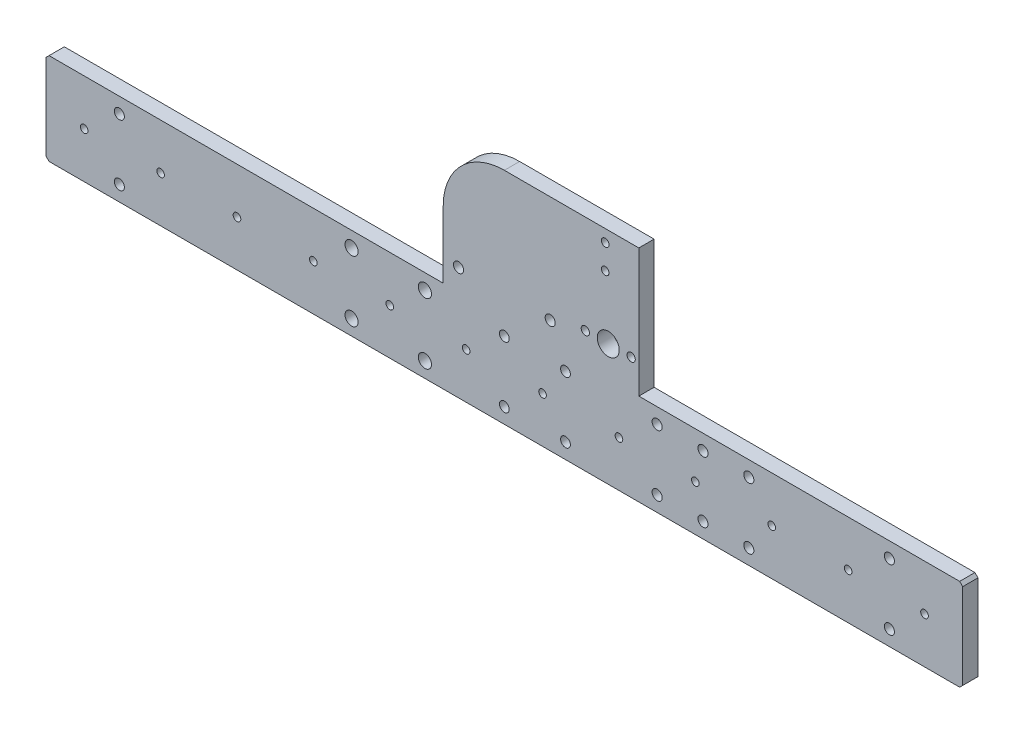
SolidWorks part; units mm, degrees
material "5052-O"
ref_plane "前基準面" through (0, 0, 0) normal (0, 0, 1) x (1, 0, 0)
ref_plane "上基準面" through (0, 0, 0) normal (0, 1, 0) x (1, 0, 0)
ref_plane "右基準面" through (0, 0, 0) normal (1, 0, 0) x (0, 0, -1)
sketch "草圖1" plane through (0, 0, 0) normal (0, 0, 1) x (1, 0, 0)
  line L1 (-150, -15) -> (150, -15)
  line L2 (-150, -15) -> (-150, 15)
  line L3 (-150, 15) -> (150, 15)
  line L4 (150, -15) -> (150, 15)
  line L5 (-150, -15) -> (150, 15) construction
  line L6 (-150, 15) -> (150, -15) construction
  point P0 (0, 0)
  dimension "D1" = 300
  dimension "D2" = 30
extrude "填料-伸長1" add sketch "草圖1" along normal blind 5
chamfer "導角1" distance 1 angle 45 4 edges at (150, -15, 2.5) (150, 15, 2.5) (-150, -15, 2.5) (-150, 15, 2.5)
hole_wizard "M3 餘隙孔1" positions "草圖7" profile "草圖8" hole size "M3" standard "Ansi Metric" end condition through all
sketch "草圖7" plane through (0, 0, 5) normal (0, 0, 1) x (1, 0, 0)
  line L0 (0, 0) -> (10, 0) construction
  line L4 (0, -10) -> (20, -10) construction
  line L5 (0, -10) -> (0, 10) construction
  line L6 (0, 10) -> (20, 10) construction
  line L7 (20, -10) -> (20, 10) construction
  line L8 (0, -10) -> (20, 10) construction
  line L9 (0, 10) -> (20, -10) construction
  point P9 (20, 10)
  point P60 (0, -10)
  point P61 (0, 10)
  point P62 (20, -10)
  dimension "D1" = 10
  dimension "D2" = 20
  dimension "D3" = 20
sketch "草圖8" plane through (20, -10, 5) normal (1, 0, 0) x (0, -1, 0)
  line L0 (0, 0) -> (0, 5)
  line L1 (0, 5) -> (1.6, 5)
  line L2 (1.6, 5) -> (1.6, 0)
  line L5 (1.6, 0) -> (0, 0)
  line L11 (0, -6.35) -> (0, 107.95) construction
  dimension "貫穿孔直徑" = 3.2
  dimension "貫穿孔深度" = 5
hole_wizard "M3x0.5 螺紋孔1" positions "草圖3" profile "草圖4" tap size "M3x0.5" standard "Ansi Metric" end condition through all
sketch "草圖3" plane through (0, 0, 5) normal (0, 0, 1) x (1, 0, 0)
  line L0 (-12.5, 0) -> (12.5, 0) construction
  point P0 (-12.5, 0)
  dimension "D1" = 25
sketch "草圖4" plane through (-12.5, 0, 5) normal (1, 0, 0) x (0, -1, 0)
  line L0 (0, 0) -> (0, 5)
  line L1 (0, 5) -> (1.25, 5)
  line L2 (1.25, 5) -> (1.25, 0)
  line L5 (1.25, 0) -> (0, 0)
  line L11 (0, -6.35) -> (0, 107.95) construction
  dimension "貫穿螺孔鑽直徑" = 2.5
  dimension "貫穿螺孔鑽深度" = 5
hole_wizard "M4x0.7 螺紋孔1" positions "草圖9" profile "草圖10" tap size "M4x0.7" standard "Ansi Metric" end condition through all
sketch "草圖9" plane through (0, 0, 5) normal (0, 0, 1) x (1, 0, 0)
  line L1 (50, -10) -> (80, -10) construction
  line L2 (50, -10) -> (50, 10) construction
  line L3 (50, 10) -> (80, 10) construction
  line L4 (80, -10) -> (80, 10) construction
  line L5 (50, -10) -> (80, 10) construction
  line L6 (50, 10) -> (80, -10) construction
  line L7 (0, 0) -> (65, 0) construction
  point P2 (80, 10)
  point P55 (50, -10)
  point P56 (50, 10)
  point P57 (80, -10)
  point P68 (65, 0)
  point P78 (65, 10)
  point P80 (65, -10)
  dimension "D1" = 30
  dimension "D2" = 20
  dimension "D3" = 65
sketch "草圖10" plane through (80, 10, 5) normal (1, 0, 0) x (0, -1, 0)
  line L0 (0, 0) -> (0, 5)
  line L1 (0, 5) -> (1.65, 5)
  line L2 (1.65, 5) -> (1.65, 0)
  line L5 (1.65, 0) -> (0, 0)
  line L11 (0, -6.35) -> (0, 107.95) construction
  dimension "砮 脸ふ苝 畖" = 3.3
  dimension "砮 脸ふ苝瞏 " = 5
hole_wizard "M4x0.7 螺紋孔2" positions "草圖11" profile "草圖12" tap size "M4x0.7" standard "Ansi Metric" end condition through all
sketch "草圖11" plane through (0, 0, 5) normal (0, 0, 1) x (1, 0, 0)
  line L0 (-150, 0) -> (-126, 0) construction
  line L1 (-150, 14) -> (-150, -14) construction
  line L4 (-126, -10) -> (-126, 10) construction
  point P9 (-126, -10)
  point P10 (-126, 10)
  dimension "D1" = 20
  dimension "D2" = 24
sketch "草圖12" plane through (-126, 10, 5) normal (1, 0, 0) x (0, -1, 0)
  line L0 (0, 0) -> (0, 5)
  line L1 (0, 5) -> (1.65, 5)
  line L2 (1.65, 5) -> (1.65, 0)
  line L5 (1.65, 0) -> (0, 0)
  line L11 (0, -6.35) -> (0, 107.95) construction
  dimension "貫穿螺孔鑽直徑" = 3.3
  dimension "貫穿螺孔鑽深度" = 5
pattern_linear "直線複製排列1" count 6 spacing 25 along (-1, 0, 0) count 7 spacing 25 along (1, 0, 0) of "M3x0.5 螺紋孔1"
mirror "鏡射1" about plane through (0, 0, 0) normal (1, 0, 0) of "M4x0.7 螺紋孔2"
sketch "草圖16" plane through (0, 0, 0) normal (0, 0, 1) x (1, 0, 0)
  line L0 (-20, 15) -> (44, 15)
  line L1 (149, 15) -> (-149, 15) construction
  line L4 (-20, 37) -> (-20, 15)
  line L5 (0, 0) -> (0, 57) construction
  line L9 (44, 15) -> (44, 57)
  line L10 (44, 57) -> (0, 57)
  arc A1 (-20, 37) -> (0, 57) centre (0, 37) cw
  point P7 (33.0842, 57)
  point P8 (38.8416, 57)
  dimension "D3" = 22
  dimension "D1" = 20
  dimension "D2" = 57
  dimension "D4" = 44
extrude "填料-伸長3" add sketch "草圖16" along normal through all
sketch "草圖13" plane through (0, 0, 0) normal (0, 0, 1) x (1, 0, 0)
  circle A1 centre (34, 24.8) radius 3.6
  point P8 (0, 0)
  dimension "D1" = 11.9701
  dimension "D2" = 7.2
  dimension "D3" = 24.8
  dimension "D4" = 34
  dimension "D5" = 34
extrude "除料-伸長2" cut sketch "草圖13" along normal through all
hole_wizard "M2.5 餘隙孔1" positions "草圖14" profile "草圖15" hole size "M2.5" standard "Ansi Metric" end condition through all
sketch "草圖14" plane through (0, 0, 5) normal (0, 0, 1) x (1, 0, 0)
  line L1 (26.5, 24.8) -> (41.5, 24.8) construction
  circle A2 centre (34, 24.8) radius 3.6 construction
  point P1 (26.5, 24.8)
  point P2 (41.5, 24.8)
  point P17 (34, 24.8)
  dimension "D1" = 15
sketch "草圖15" plane through (26.5, 24.8, 5) normal (1, 0, 0) x (0, -1, 0)
  line L0 (0, 0) -> (0, 5)
  line L1 (0, 5) -> (1.35, 5)
  line L2 (1.35, 5) -> (1.35, 0)
  line L5 (1.35, 0) -> (0, 0)
  line L11 (0, -6.35) -> (0, 107.95) construction
  dimension "貫穿孔直徑" = 2.7
  dimension "貫穿孔深度" = 5
hole_wizard "M4x0.7 螺紋孔3" positions "草圖19" profile "草圖20" tap size "M4x0.7" standard "Ansi Metric" end condition through all
sketch "草圖19" plane through (0, 0, 5) normal (0, 0, 1) x (1, 0, 0)
  line L0 (0, 57) -> (0, 22) construction
  line L4 (-15, 22) -> (15, 22) construction
  point P9 (-15, 22)
  point P10 (15, 22)
  point P17 (0, 0)
  point P18 (0, 53.6959)
  dimension "D1" = 30
  dimension "D2" = 22
sketch "草圖20" plane through (15, 22, 5) normal (1, 0, 0) x (0, -1, 0)
  line L0 (0, 0) -> (0, 5)
  line L1 (0, 5) -> (1.65, 5)
  line L2 (1.65, 5) -> (1.65, 0)
  line L5 (1.65, 0) -> (0, 0)
  line L11 (0, -6.35) -> (0, 107.95) construction
  dimension "貫穿螺孔鑽直徑" = 3.3
  dimension "貫穿螺孔鑽深度" = 5
hole_wizard "M4 餘隙孔1" positions "草圖21" profile "草圖22" hole size "M4" standard "Ansi Metric" end condition through all
sketch "草圖21" plane through (0, 0, 5) normal (0, 0, 1) x (1, 0, 0)
  line L0 (0, 0) -> (-38, 0) construction
  line L4 (-50, -10) -> (-26, -10) construction
  line L5 (-50, -10) -> (-50, 10) construction
  line L6 (-50, 10) -> (-26, 10) construction
  line L7 (-26, -10) -> (-26, 10) construction
  line L8 (-50, -10) -> (-26, 10) construction
  line L9 (-50, 10) -> (-26, -10) construction
  point P11 (-26, 10)
  point P60 (-50, -10)
  point P61 (-50, 10)
  point P62 (-26, -10)
  dimension "D1" = 38
  dimension "D2" = 24
  dimension "D3" = 20
sketch "草圖22" plane through (-26, -10, 5) normal (1, 0, 0) x (0, -1, 0)
  line L0 (0, 0) -> (0, 5)
  line L1 (0, 5) -> (2.15, 5)
  line L2 (2.15, 5) -> (2.15, 0)
  line L5 (2.15, 0) -> (0, 0)
  line L11 (0, -6.35) -> (0, 107.95) construction
  dimension "貫穿孔直徑" = 4.3
  dimension "貫穿孔深度" = 5
hole_wizard "M3x0.5 螺紋孔2" positions "草圖23" profile "草圖24" tap size "M3x0.5" standard "Ansi Metric" end condition through all
sketch "草圖23" plane through (0, 0, 5) normal (0, 0, 1) x (1, 0, 0)
  line L0 (33, 53) -> (33, 45) construction
  line L3 (44, 15) -> (44, 57) construction
  line L4 (44, 57) -> (0, 57) construction
  point P0 (33, 53)
  point P1 (33, 45)
  dimension "D1" = 11
  dimension "D2" = 8
  dimension "D3" = 4
sketch "草圖24" plane through (33, 53, 5) normal (1, 0, 0) x (0, -1, 0)
  line L0 (0, 0) -> (0, 5)
  line L1 (0, 5) -> (1.25, 5)
  line L2 (1.25, 5) -> (1.25, 0)
  line L5 (1.25, 0) -> (0, 0)
  line L11 (0, -6.35) -> (0, 107.95) construction
  dimension "貫穿螺孔鑽直徑" = 2.5
  dimension "貫穿螺孔鑽深度" = 5
